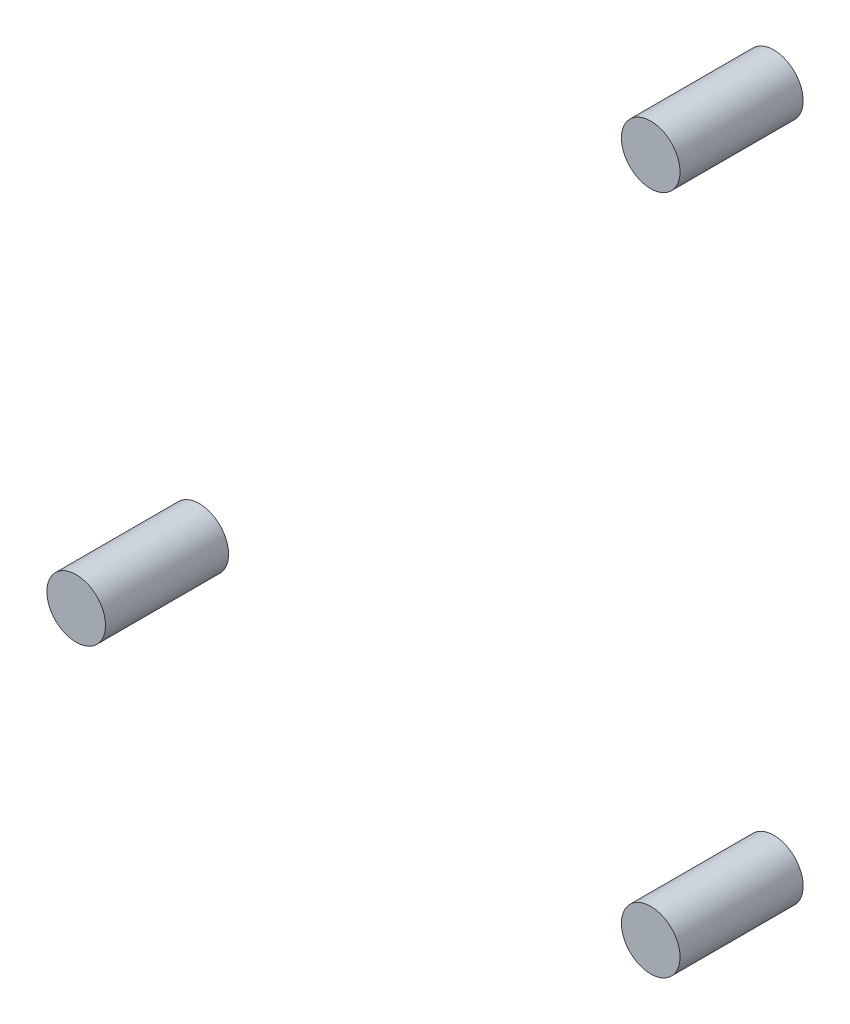
SolidWorks part; units mm, degrees
ref_plane "Front Plane" through (0, 0, 0) normal (0, 0, 1) x (1, 0, 0)
ref_plane "Top Plane" through (0, 0, 0) normal (0, 1, 0) x (1, 0, 0)
ref_plane "Right Plane" through (0, 0, 0) normal (1, 0, 0) x (0, 0, -1)
sketch "Sketch1" plane through (0, 0, 0) normal (0, 0, 1) x (1, 0, 0)
  circle A0 centre (37.396, 192.909) radius 2.5
  circle A1 centre (86.396, 192.909) radius 2.5
  circle A2 centre (86.396, 250.909) radius 2.5
  dimension "D1" = 5
extrude "Boss-Extrude1" add sketch "Sketch1" along normal up to surface (10.5 mm away)
